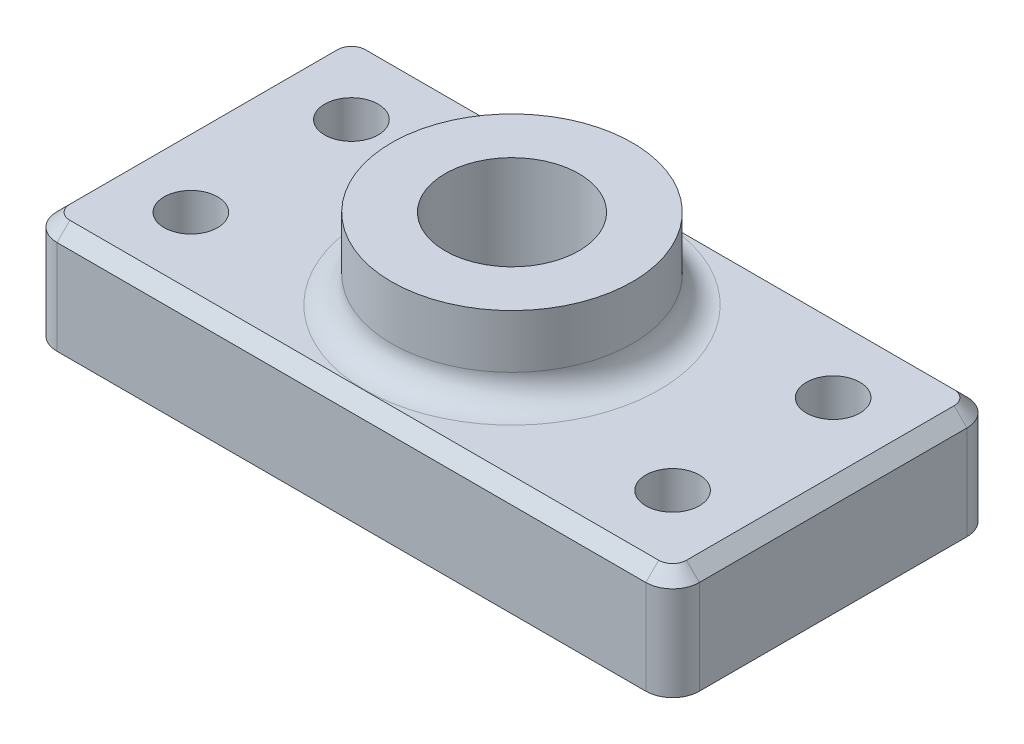
SolidWorks part; units mm, degrees
ref_plane "Front Plane" through (0, 0, 0) normal (0, 0, 1) x (1, 0, 0)
ref_plane "Top Plane" through (0, 0, 0) normal (0, 1, 0) x (1, 0, 0)
ref_plane "Right Plane" through (0, 0, 0) normal (1, 0, 0) x (0, 0, -1)
sketch "Sketch1" plane through (0, 0, 0) normal (0, 1, 0) x (1, 0, 0)
  line L0 (0, 1098.5986) -> (0, 0) construction
  line L1 (3000, -1500) -> (-3000, -1500)
  line L2 (3000, -1500) -> (3000, 1500)
  line L3 (3000, 1500) -> (-3000, 1500)
  line L4 (-3000, -1500) -> (-3000, 1500)
  line L5 (3000, -1500) -> (-3000, 1500) construction
  line L6 (3000, 1500) -> (-3000, -1500) construction
  line L7 (0, 0) -> (-2401.9754, 0) construction
  circle A0 centre (-2250, 750) radius 250
  circle A1 centre (2250, 750) radius 250
  circle A2 centre (-2250, -750) radius 250
  circle A3 centre (2250, -750) radius 250
  point P0 (0, 0)
  dimension "D3" = 500
  dimension "D1" = 3000
  dimension "D2" = 6000
  dimension "D4" = 750
  dimension "D5" = 750
extrude "Boss-Extrude1" add sketch "Sketch1" along normal blind 1000
sketch "Sketch2" plane through (0, 1000, 0) normal (0, 1, 0) x (1, 0, 0)
  circle A0 centre (0, 0) radius 625
  circle A1 centre (0, 0) radius 1125
  dimension "D1" = 2250
  dimension "D2" = 1250
extrude "Boss-Extrude2" add sketch "Sketch2" along normal blind 750
sketch "Sketch4" plane through (0, 1000, 0) normal (0, 1, 0) x (1, 0, 0)
  circle A0 centre (0, 0) radius 625
extrude "Cut-Extrude1" cut sketch "Sketch4" against normal through all
fillet "Fillet1" radius 250 1 edges at (0, 1000, 1125)
fillet "Fillet2" radius 250 4 edges at (-3000, 500, -1500) (3000, 500, -1500) (3000, 500, 1500) (-3000, 500, 1500)
chamfer "Chamfer1" distance 120 angle 45 8 edges at (0, 1000, -1500) (-2926.7767, 1000, -1426.7767) (2926.7767, 1000, -1426.7767) (-3000, 1000, 0) (3000, 1000, 0) (-2926.7767, 1000, 1426.7767) (2926.7767, 1000, 1426.7767) (0, 1000, 1500)
